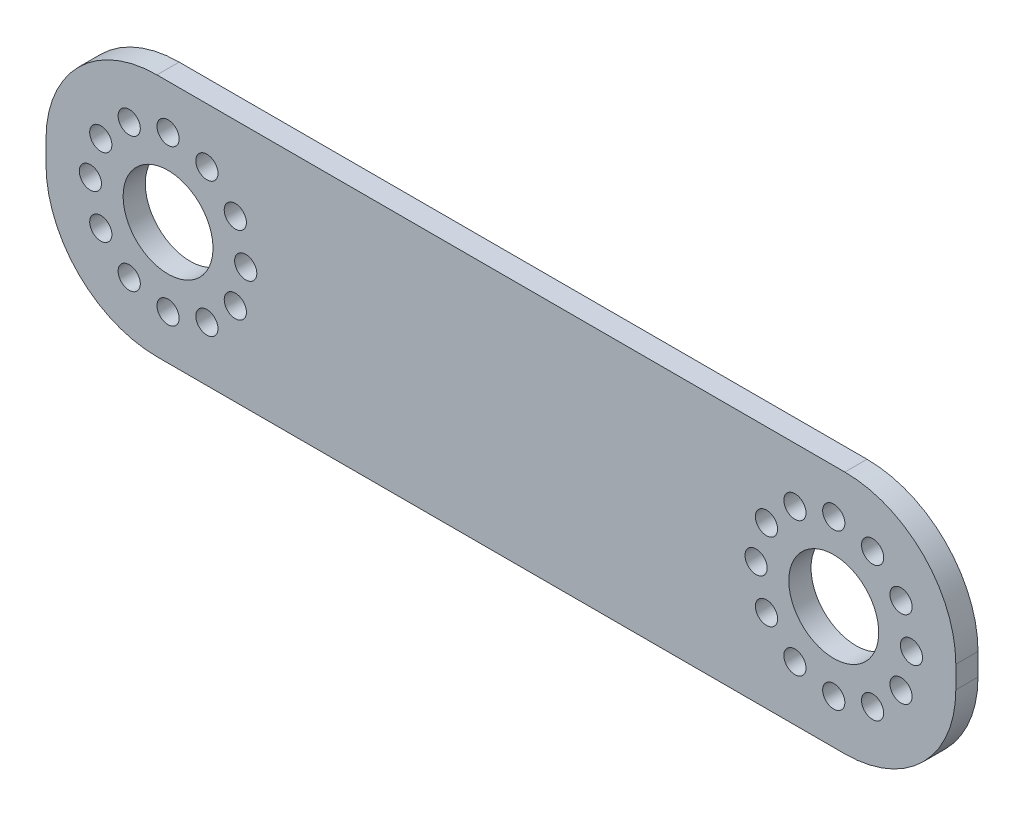
SolidWorks part; units mm, degrees
ref_plane "Plan de face" through (0, 0, 0) normal (0, 0, 1) x (1, 0, 0)
ref_plane "Plan de dessus" through (0, 0, 0) normal (0, 1, 0) x (1, 0, 0)
ref_plane "Plan de droite" through (0, 0, 0) normal (1, 0, 0) x (0, 0, -1)
sketch "Esquisse2" plane through (0, 0, 0) normal (0, 0, -1) x (-1, 0, 0)
  line L0 (-82, -11) -> (0, -11)
  line L2 (0, -11) -> (0, 11)
  line L3 (0, 11) -> (-82, 11)
  line L4 (-82, 11) -> (-82, -11)
  line L5 (-95.5557, 0) -> (0, 0) construction
  circle B0 centre (-11, 0) radius 4.05
  circle B1 centre (-4, 0) radius 1
  circle B2 centre (-4.9378, -3.5) radius 1
  circle B3 centre (-7.5, -6.0622) radius 1
  circle B4 centre (-11, -7) radius 1
  circle B5 centre (-14.5, -6.0622) radius 1
  circle B6 centre (-17.0622, -3.5) radius 1
  circle B7 centre (-18, 0) radius 1
  circle B8 centre (-17.0622, 3.5) radius 1
  circle B9 centre (-14.5, 6.0622) radius 1
  circle B10 centre (-11, 7) radius 1
  circle B11 centre (-7.5, 6.0622) radius 1
  circle B12 centre (-4.9378, 3.5) radius 1
  circle B13 centre (-71, 0) radius 4.05
  circle B14 centre (-64, 0) radius 1
  circle B15 centre (-64.9378, -3.5) radius 1
  circle B16 centre (-67.5, -6.0622) radius 1
  circle B17 centre (-71, -7) radius 1
  circle B18 centre (-74.5, -6.0622) radius 1
  circle B19 centre (-77.0622, -3.5) radius 1
  circle B20 centre (-78, 0) radius 1
  circle B21 centre (-77.0622, 3.5) radius 1
  circle B22 centre (-74.5, 6.0622) radius 1
  circle B23 centre (-71, 7) radius 1
  circle B24 centre (-67.5, 6.0622) radius 1
  circle B25 centre (-64.9378, 3.5) radius 1
  dimension "D1" = 22
  dimension "D2" = 11
  dimension "D3" = 11
  dimension "D4" = 60
sketch_block_instance "Block1-1"
sketch_block "Block1" parameters "D2"=2, "D3"=8.1, "D1"=7
sketch_block_instance "Block1-2"
extrude "Boss.-Extru.1" add sketch "Esquisse2" against normal blind 2
fillet "Congé1" radius 10 4 edges at (0, -11, 1) (0, 11, 1) (82, 11, 1) (82, -11, 1)
